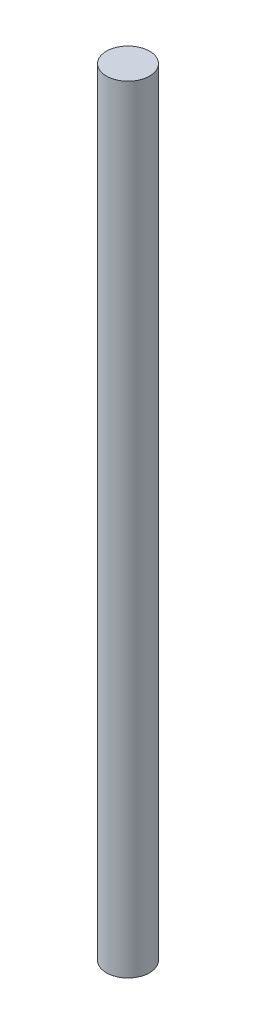
SolidWorks part; units mm, degrees
ref_plane "Front Plane" through (0, 0, 0) normal (0, 0, 1) x (1, 0, 0)
ref_plane "Top Plane" through (0, 0, 0) normal (0, 1, 0) x (1, 0, 0)
ref_plane "Right Plane" through (0, 0, 0) normal (1, 0, 0) x (0, 0, -1)
sketch "Sketch1" plane through (0, 0, 0) normal (0, 1, 0) x (1, 0, 0)
  circle A0 centre (0, 0) radius 1
  dimension "D1" = 2
extrude "Boss-Extrude1" add sketch "Sketch1" along normal blind 36
